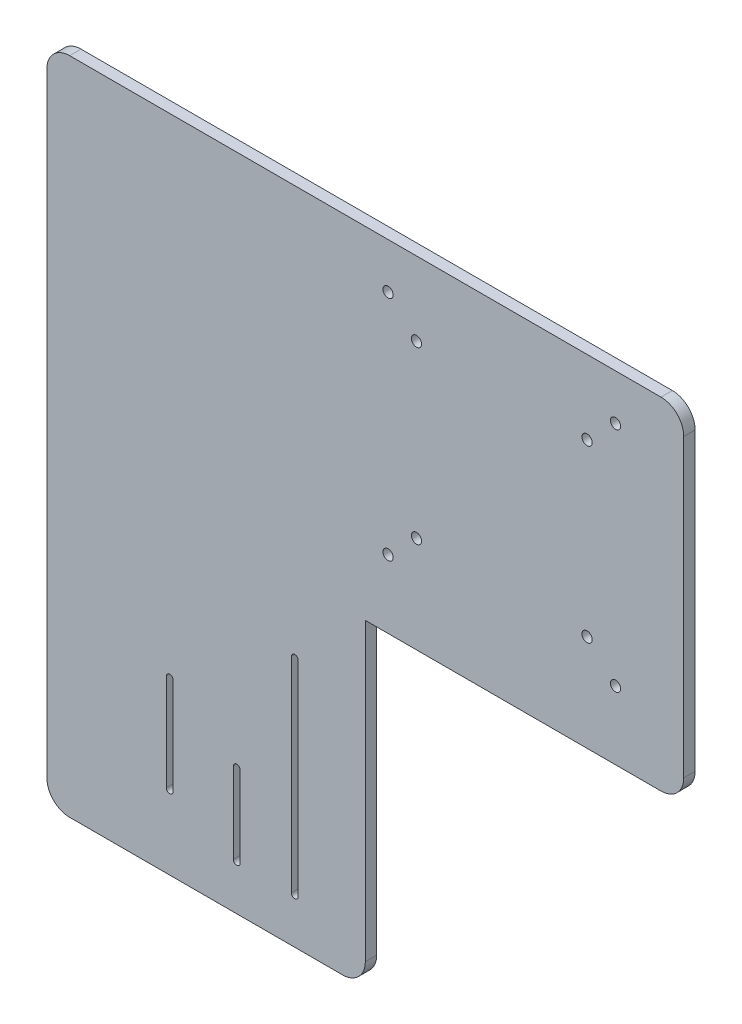
SolidWorks part; units mm, degrees
ref_plane "Front Plane" through (0, 0, 0) normal (0, 0, 1) x (1, 0, 0)
ref_plane "Top Plane" through (0, 0, 0) normal (0, 1, 0) x (1, 0, 0)
ref_plane "Right Plane" through (0, 0, 0) normal (1, 0, 0) x (0, 0, -1)
sketch "Sketch1" plane through (0, 0, 0) normal (0, 0, 1) x (1, 0, 0)
  line L0 (-10, 0) -> (-270, 0)
  line L1 (-280, -10) -> (-280, -280)
  line L2 (-270, -290) -> (-150, -290)
  line L3 (-140, -280) -> (-140, -150)
  line L4 (-140, -150) -> (-10, -150)
  line L5 (0, -140) -> (0, -10)
  arc A0 (-270, -290) -> (-280, -280) centre (-270, -280) cw
  arc A1 (-150, -290) -> (-140, -280) centre (-150, -280) ccw
  arc A2 (0, -140) -> (-10, -150) centre (-10, -140) cw
  arc A3 (-10, 0) -> (0, -10) centre (-10, -10) cw
  arc A4 (-280, -10) -> (-270, 0) centre (-270, -10) cw
  point P9 (-280, -290)
  point P12 (-140, -290)
  point P15 (0, -150)
  point P18 (0, 0)
  dimension "D3" = 150
  dimension "D4" = 10
  dimension "D1" = 140
  dimension "D2" = 140
extrude "Boss-Extrude1" add sketch "Sketch1" along normal blind 5
hole_wizard "M4 Clearance Hole1" positions "Sketch3" profile "Sketch2" hole size "M4" standard "ANSI Metric"
sketch "Sketch3" plane through (0, 0, 5) normal (0, 0, 1) x (1, 0, 0)
  line L0 (-140, -150) -> (-10, -150) construction
  line L1 (-140, -280) -> (-140, -150) construction
  point P6 (-130, -120)
  point P66 (-30, -120)
  point P67 (-30, -20)
  point P68 (-130, -20)
  point P69 (-117.5, -107.5)
  point P78 (-42.5, -107.5)
  point P79 (-42.5, -32.5)
  point P80 (-117.5, -32.5)
  dimension "D1" = 2
  dimension "D2" = 2
  dimension "D3" = 30
  dimension "D4" = 10
  dimension "D5" = 12.5
  dimension "D6" = 12.5
  dimension "D7" = 2
  dimension "D8" = 2
sketch "Sketch2" plane through (-130, -120, 5) normal (1, 0, 0) x (0, -1, 0)
  line L0 (0, 0) -> (0, 11.3519)
  line L1 (0, 11.3519) -> (2.25, 10)
  line L2 (2.25, 10) -> (2.25, 0)
  line L5 (2.25, 0) -> (0, 0)
  line L10 (0, 11.3519) -> (-2.25, 10) construction
  line L11 (0, -6.35) -> (0, 107.95) construction
  dimension "Hole Dia." = 4.5
  dimension "Hole Depth" = 10
  dimension "Drill Angle" = 118
sketch "Sketch4" plane through (0, 0, 5) normal (0, 0, 1) x (1, 0, 0)
  line L1 (-171, -270) -> (-171, -180) construction
  line L2 (-172.5, -270) -> (-172.5, -180)
  line L3 (-169.5, -270) -> (-169.5, -180)
  line L4 (-196.5, -270) -> (-196.5, -234.5) construction
  line L5 (-198, -270) -> (-198, -234.5)
  line L6 (-195, -270) -> (-195, -234.5)
  line L7 (-226, -257.5) -> (-226, -215) construction
  line L8 (-227.5, -257.5) -> (-227.5, -215)
  line L9 (-224.5, -257.5) -> (-224.5, -215)
  line L10 (-140, -280) -> (-140, -150) construction
  line L11 (-270, -290) -> (-150, -290) construction
  arc A0 (-172.5, -270) -> (-169.5, -270) centre (-171, -270) ccw
  arc A1 (-169.5, -180) -> (-172.5, -180) centre (-171, -180) ccw
  arc A2 (-198, -270) -> (-195, -270) centre (-196.5, -270) ccw
  arc A3 (-195, -234.5) -> (-198, -234.5) centre (-196.5, -234.5) ccw
  arc A4 (-227.5, -257.5) -> (-224.5, -257.5) centre (-226, -257.5) ccw
  arc A5 (-224.5, -215) -> (-227.5, -215) centre (-226, -215) ccw
  point P2 (-171, -225)
  point P7 (-196.5, -252.25)
  point P14 (-226, -236.25)
  dimension "D7" = 1.5
  dimension "D1" = 31
  dimension "D2" = 20
  dimension "D3" = 90
  dimension "D4" = 12.5
  dimension "D5" = 35.5
  dimension "D6" = 42.5
  dimension "D8" = 25.5
  dimension "D9" = 55
extrude "Cut-Extrude1" cut sketch "Sketch4" against normal through all
